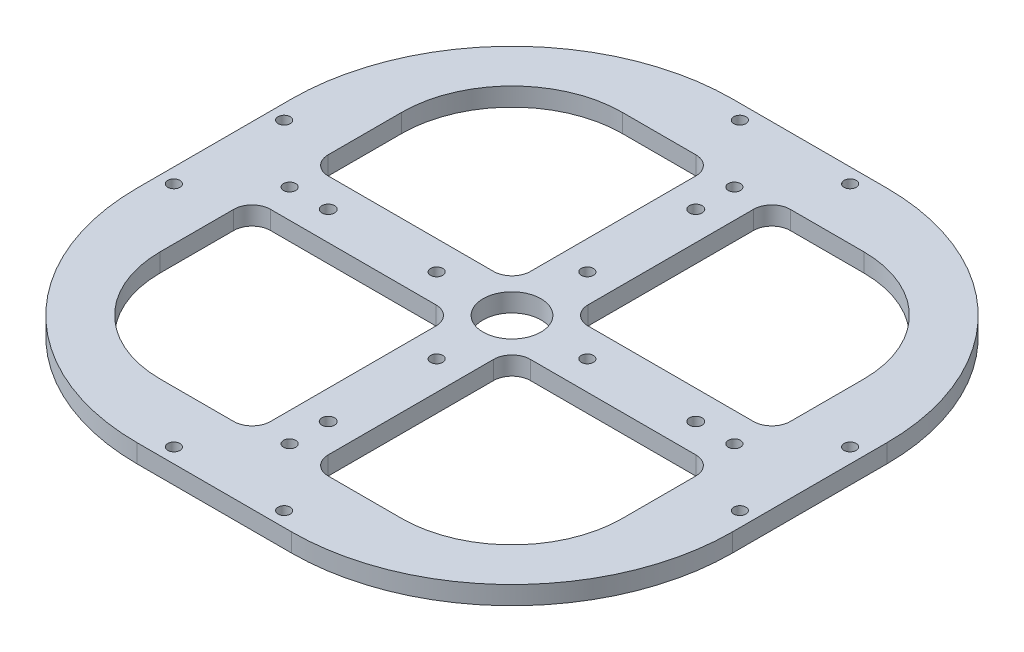
SolidWorks part; units mm, degrees
ref_plane "Front Plane" through (0, 0, 0) normal (0, 0, 1) x (1, 0, 0)
ref_plane "Top Plane" through (0, 0, 0) normal (0, 1, 0) x (1, 0, 0)
ref_plane "Right Plane" through (0, 0, 0) normal (1, 0, 0) x (0, 0, -1)
sketch "Sketch1" plane through (0, 0, 0) normal (0, 1, 0) x (1, 0, 0)
  line L0 (0, 0) -> (63.5, 0) construction
  line L1 (0, 0) -> (76.9579, 0) construction
  line L3 (-102.87, -102.87) -> (102.87, -102.87)
  line L4 (-102.87, -102.87) -> (-102.87, 102.87)
  line L5 (-102.87, 102.87) -> (102.87, 102.87)
  line L6 (102.87, -102.87) -> (102.87, 102.87)
  line L7 (-102.87, -102.87) -> (102.87, 102.87) construction
  line L8 (-102.87, 102.87) -> (102.87, -102.87) construction
  circle A1 centre (63.5, 0) radius 2.2
  circle A2 centre (0, -63.5) radius 2.2
  circle A3 centre (-63.5, 0) radius 2.2
  circle A4 centre (0, 63.5) radius 2.2
  point P14 (0, 0)
  dimension "D3" = 4.4
  dimension "D2" = 63.5
  dimension "D4" = 0
  dimension "D1" = 205.74
extrude "Boss-Extrude1" add sketch "Sketch1" along normal blind 6.35
sketch "Sketch5" plane through (0, 0, 0) normal (0, 0, 1) x (1, 0, 0)
  line L0 (0, 0) -> (0, 41.1667) construction
sketch "Sketch3" plane through (0, 6.35, 0) normal (0, 1, 0) x (1, 0, 0)
  circle A0 centre (0, 0) radius 10
  dimension "D1" = 20
extrude "Cut-Extrude2" cut sketch "Sketch3" against normal through all
sketch "Sketch4" plane through (0, 6.35, 0) normal (0, 1, 0) x (1, 0, 0)
  line L4 (-102.87, 102.87) -> (0, 0) construction
  line L5 (-79.8263, 9.9763) -> (-9.9763, 9.9763)
  line L6 (-79.8263, 9.9763) -> (-79.8263, 79.8263)
  line L7 (-79.8263, 79.8263) -> (-9.9763, 79.8263)
  line L8 (-9.9763, 9.9763) -> (-9.9763, 79.8263)
  line L9 (-79.8263, 9.9763) -> (-9.9763, 79.8263) construction
  line L10 (-79.8263, 79.8263) -> (-9.9763, 9.9763) construction
  point P0 (-44.9013, 44.9013)
  dimension "D1" = 69.85
  dimension "D2" = 63.5
extrude "Cut-Extrude3" cut sketch "Sketch4" against normal through all
fillet "Fillet4" radius 6.35 3 edges at (-9.9763, 3.175, -79.8263) (-9.9763, 3.175, -9.9763) (-79.8263, 3.175, -9.9763)
pattern_circular "CirPattern6" count 4 over 360 about axis through (0, 0, 0) along (0, 1, 0) of "Fillet4", "Cut-Extrude3"
fillet "Fillet8" radius 38.1 4 edges at (-79.8263, 3.175, 79.8263) (79.8263, 3.175, 79.8263) (79.8263, 3.175, -79.8263) (-79.8263, 3.175, -79.8263)
fillet "Fillet9" radius 76.2 4 edges at (102.87, 3.175, 102.87) (102.87, 3.175, -102.87) (-102.87, 3.175, -102.87) (-102.87, 3.175, 102.87)
sketch "Sketch10" plane through (0, 6.35, 0) normal (0, 1, 0) x (1, 0, 0)
  circle A0 centre (19.05, -97.79) radius 1.85 construction
  circle A1 centre (-19.05, -97.79) radius 1.85 construction
  circle A2 centre (0, -76.835) radius 1.85 construction
  circle A3 centre (0, -26.035) radius 1.85 construction
  circle A4 centre (19.05, -97.79) radius 1.85 construction
  circle A5 centre (-19.05, -97.79) radius 1.85 construction
  circle A6 centre (0, -76.835) radius 1.85 construction
  circle A7 centre (0, -26.035) radius 1.85 construction
  circle A8 centre (0, -26.035) radius 2.1
  circle A9 centre (0, -76.835) radius 2.1
  circle A10 centre (-19.05, -97.79) radius 2.1
  circle A11 centre (19.05, -97.79) radius 2.1
  dimension "D1" = 4.2
extrude "Cut-Extrude6" cut sketch "Sketch10" against normal through all
sketch "Sketch11" plane through (0, 0, 0) normal (0, -1, 0) x (1, 0, 0)
  circle A0 centre (-19.05, 97.79) radius 4
  circle A1 centre (19.05, 97.79) radius 4
  circle A2 centre (0, 76.835) radius 4
  circle A3 centre (0, 26.035) radius 4
  dimension "D1" = 8
extrude "Cut-Extrude7" cut sketch "Sketch11" against normal blind 3
pattern_circular "CirPattern4" count 4 over 360 about axis through (0, 0, 0) along (0, 1, 0) of "Cut-Extrude6", "Cut-Extrude7"
equation "\"D3@Sketch1\"=4.4mm"
equation "\"D1@Sketch3\"=20mm"
equation "\"D1@Sketch10\"=4.2mm"
equation "\"D1@Sketch11\"=8mm"
equation "\"D1@Cut-Extrude7\"=3mm"
